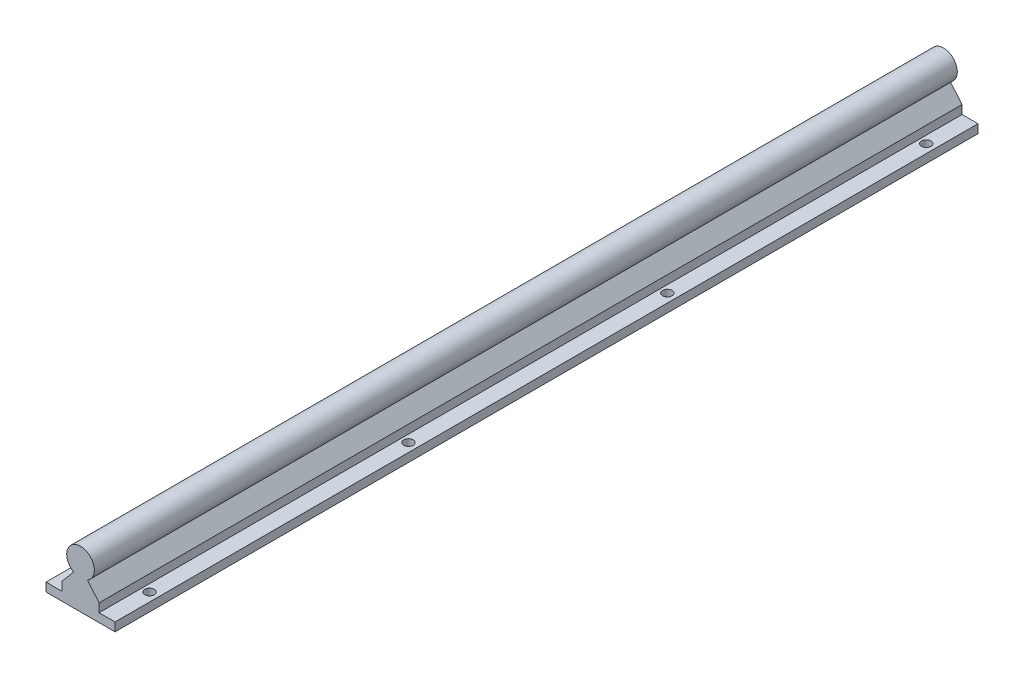
SolidWorks part; units mm, degrees
ref_plane "Front Plane" through (0, 0, 0) normal (0, 0, 1) x (1, 0, 0)
ref_plane "Top Plane" through (0, 0, 0) normal (0, 1, 0) x (1, 0, 0)
ref_plane "Right Plane" through (0, 0, 0) normal (1, 0, 0) x (0, 0, -1)
sketch "Sketch1" plane through (0, 0, 0) normal (0, 0, 1) x (1, 0, 0)
  line L0 (-21.6204, 0) -> (18.3796, 0)
  line L1 (18.3796, 0) -> (18.3796, 5)
  line L2 (18.3796, 5) -> (9.1526, 5)
  line L3 (9.1526, 5) -> (9.1526, 10)
  line L4 (-21.6204, 0) -> (-21.6204, 5)
  line L5 (-21.6204, 5) -> (-12.3934, 5)
  line L6 (-12.3934, 5) -> (-12.3934, 10)
  line L7 (-12.3934, 10) -> (-5.6204, 18.0718)
  line L8 (9.1526, 10) -> (2.3796, 18.0718)
  arc A0 (-5.6204, 18.0718) -> (2.3796, 18.0718) centre (-1.6204, 25) cw
  dimension "D6" = 8
  dimension "D1" = 40
  dimension "D2" = 5
  dimension "D3" = 8
  dimension "D4" = 5
  dimension "D5" = 80
  dimension "D7" = 25
extrude "Boss-Extrude1" add sketch "Sketch1" along normal blind 500
sketch "Sketch2" plane through (0, 0, 0) normal (0, 1, 0) x (1, 0, 0)
  line L0 (-21.6204, -500) -> (-21.6204, 0) construction
  line L1 (-12.3934, 0) -> (-21.6204, 0) construction
  line L2 (-12.3934, -500) -> (-21.6204, -500) construction
  circle A0 centre (-16.6204, -475) radius 2.75
  circle A1 centre (13.3796, -475) radius 2.75
  circle A2 centre (-16.6204, -325) radius 2.75
  circle A3 centre (13.3796, -325) radius 2.75
  circle A4 centre (-16.6204, -175) radius 2.75
  circle A5 centre (13.3796, -175) radius 2.75
  circle A6 centre (-16.6204, -25) radius 2.75
  circle A7 centre (13.3796, -25) radius 2.75
  point P4 (0, 0)
  point P5 (-16.8329, -494.0064)
  point P12 (0, 0)
  point P21 (13.3796, -210.9569)
  point P22 (0, 0)
  point P23 (0, 0)
  dimension "D1" = 5.5
  dimension "D2" = 30
  dimension "D5" = 150
  dimension "D3" = 5
  dimension "D4" = 150
  dimension "D6" = 25
  dimension "D7" = 150
  dimension "D8" = 25
extrude "Cut-Extrude1" cut sketch "Sketch2" along normal through all
